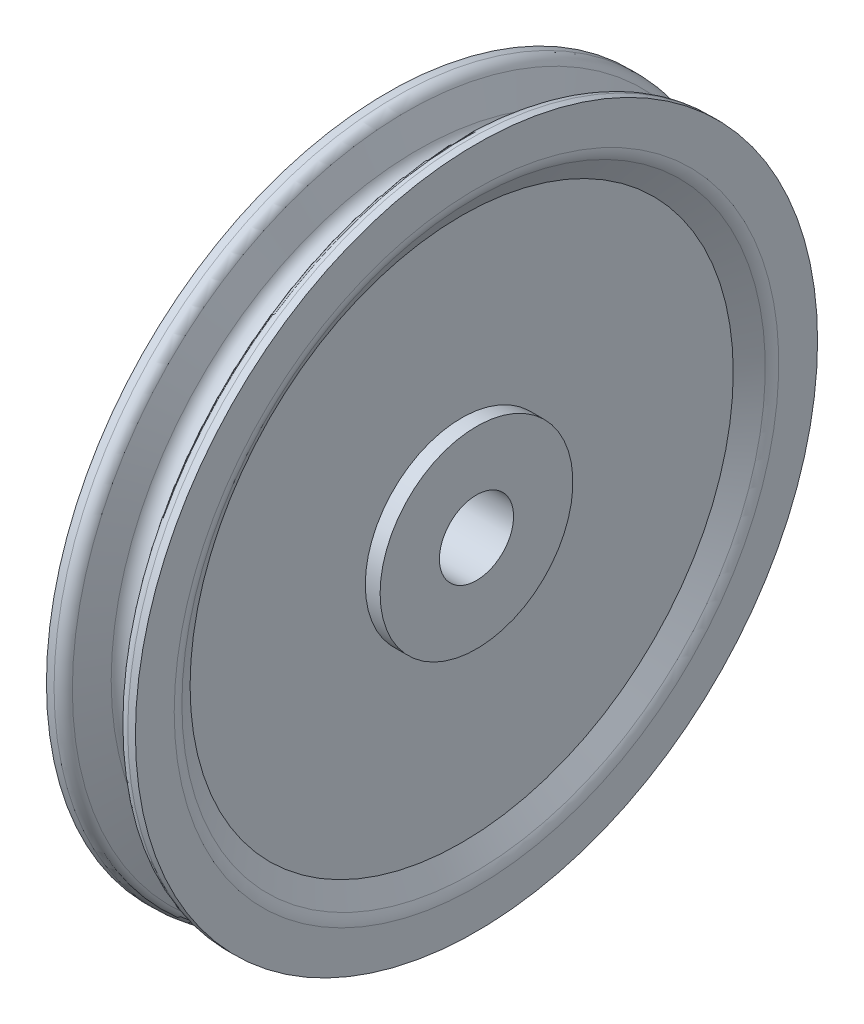
SolidWorks part; units mm, degrees
ref_plane "Front Plane" through (0, 0, 0) normal (0, 0, 1) x (1, 0, 0)
ref_plane "Top Plane" through (0, 0, 0) normal (0, 1, 0) x (1, 0, 0)
ref_plane "Right Plane" through (0, 0, 0) normal (1, 0, 0) x (0, 0, -1)
sketch "Sketch1" plane through (0, 0, 0) normal (0, 0, 1) x (1, 0, 0)
  line L0 (-36.2117, 0) -> (45.4738, 0) construction
  line L1 (-15, 12.5) -> (15, 12.5)
  line L2 (-15, 100) -> (-14.7317, 100)
  line L3 (-15, 115) -> (-12.4273, 115)
  line L5 (-4.8966, 103.2718) -> (-8.7317, 112.5307)
  line L6 (4.8966, 103.2718) -> (8.7317, 112.5307)
  line L7 (-15, 115) -> (-15, 101.9196)
  line L8 (15, 115) -> (15, 101.9196)
  line L9 (12.4273, 115) -> (15, 115)
  line L11 (-14.0209, 98.3489) -> (-10, 91.5688)
  line L12 (14.0209, 98.3489) -> (10, 91.5688)
  line L13 (14.7317, 100) -> (15, 100)
  line L14 (-10, 91.5688) -> (-10, 32.5)
  line L15 (10, 91.5688) -> (10, 32.5)
  line L16 (-15, 32.5) -> (-10, 32.5)
  line L17 (10, 32.5) -> (15, 32.5)
  line L18 (-15, 32.5) -> (-15, 12.5)
  line L19 (15, 32.5) -> (15, 12.5)
  arc A0 (-4.8966, 103.2718) -> (4.8966, 103.2718) centre (0, 105.3) ccw
  arc A1 (12.4273, 115) -> (8.7317, 112.5307) centre (12.4273, 111) ccw
  arc A2 (-8.7317, 112.5307) -> (-12.4273, 115) centre (-12.4273, 111) ccw
  arc A3 (-15, 101.9196) -> (-14.0209, 98.3489) centre (-8, 101.9196) ccw
  arc A4 (15, 101.9196) -> (14.0209, 98.3489) centre (8, 101.9196) cw
  point P8 (0, 100)
  point P21 (9.7546, 115)
  point P24 (-9.7546, 115)
  point P27 (0, 91.5688)
  point P38 (0, 12.5)
  dimension "D5" = 10.6
  dimension "D6" = 45
  dimension "D7" = 4
  dimension "D9" = 7
  dimension "D1" = 30
  dimension "D2" = 30
  dimension "D3" = 100
  dimension "D4" = 15
  dimension "D8" = 20
  dimension "D10" = 12.5
  dimension "D11" = 20
revolve "Revolve-Thin2" add sketch "Sketch1" angle 360 about L0
